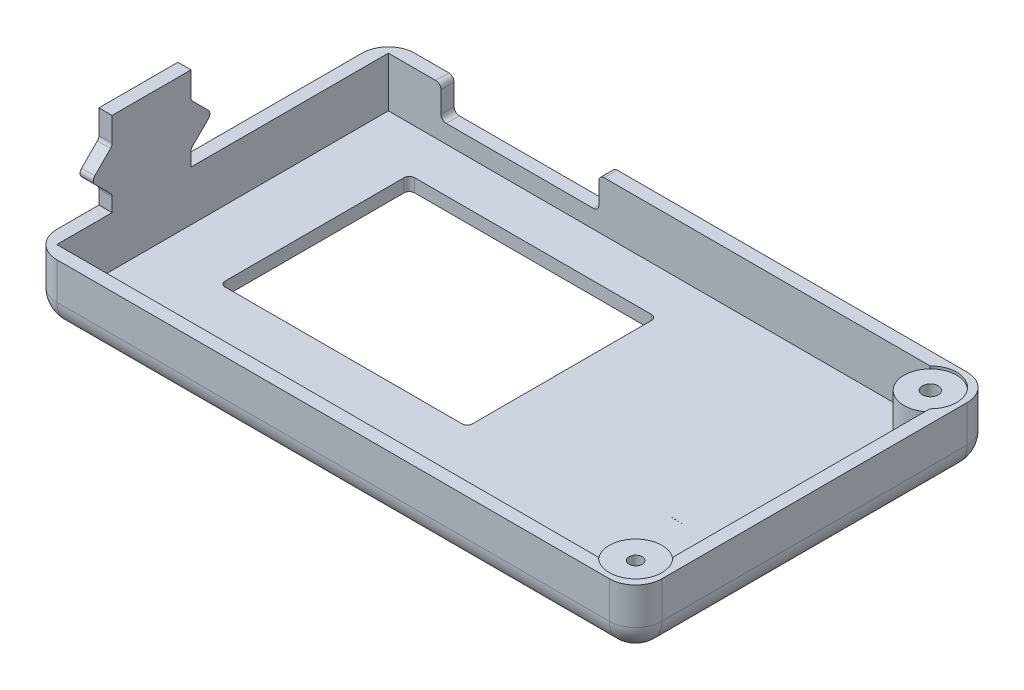
SolidWorks part; units mm, degrees
ref_plane "Front Plane" through (0, 0, 0) normal (0, 0, 1) x (1, 0, 0)
ref_plane "Top Plane" through (0, 0, 0) normal (0, 1, 0) x (1, 0, 0)
ref_plane "Right Plane" through (0, 0, 0) normal (1, 0, 0) x (0, 0, -1)
sketch "Sketch1" plane through (0, 0, 0) normal (0, 1, 0) x (1, 0, 0)
  line L1 (-57.5, -34) -> (57.5, -34)
  line L2 (-57.5, -34) -> (-57.5, 34)
  line L3 (-57.5, 34) -> (57.5, 34)
  line L4 (57.5, -34) -> (57.5, 34)
  line L5 (-57.5, -34) -> (57.5, 34) construction
  line L6 (-57.5, 34) -> (57.5, -34) construction
  point P0 (0, 0)
  dimension "D1" = 115
  dimension "D2" = 68
extrude "Boss-Extrude1" add sketch "Sketch1" along normal blind 28
shell "Shell2" thickness 2.5
sketch "Sketch9" plane through (-57.5, 0, 0) normal (-1, 0, 0) x (0, 0, 1)
  line L0 (-34, 12) -> (6, 12)
  line L1 (-34, 28) -> (-34, 0) construction
  line L2 (6, 12) -> (6, 15)
  line L3 (6, 15) -> (2, 19)
  line L4 (2, 19) -> (6, 23)
  line L5 (6, 23) -> (6, 28)
  line L6 (-34, 28) -> (34, 28) construction
  line L7 (6, 28) -> (21, 28)
  line L8 (21, 28) -> (21, 23)
  line L9 (21, 15) -> (25, 19)
  line L10 (25, 19) -> (21, 23)
  line L11 (21, 15) -> (21, 12)
  line L12 (21, 12) -> (34, 12)
  line L13 (34, 28) -> (34, 0) construction
  line L14 (34, 12) -> (34, 34)
  line L15 (34, 34) -> (-34, 34)
  line L16 (-34, 34) -> (-34, 12)
  line L17 (-34, 0) -> (34, 0) construction
  dimension "D1" = 3
  dimension "D2" = 12
  dimension "D3" = 4
  dimension "D4" = 15
  dimension "D5" = 22
  dimension "D6" = 4
  dimension "D7" = 13
extrude "Cut-Extrude8" cut sketch "Sketch9" against normal through all
sketch "Sketch10" plane through (57.5, 0, 0) normal (1, 0, 0) x (0, 0, -1)
  line L0 (-24.9917, 12) -> (1.2258, 12)
  line L1 (-21, 12) -> (-34, 12) construction
  line L2 (34, 12) -> (-6, 12) construction
  line L3 (1.2258, 12) -> (1.2258, 35)
  line L4 (1.2258, 35) -> (-24.9917, 35)
  line L5 (-24.9917, 35) -> (-24.9917, 12)
  dimension "D1" = 23
extrude "Cut-Extrude9" cut sketch "Sketch10" against normal up to next
fillet "Fillet3" radius 5 8 edges at (0, 0, 34) (57.5, 6, 34) (57.5, 0, 0) (57.5, 6, -34) (0, 0, -34) (-57.5, 6, -34) (-57.5, 0, 0) (-57.5, 6, 34)
fillet "Fillet4" radius 1 6 edges at (-56.25, 19, 25) (-56.25, 23, 21) (-56.25, 15, 21) (-56.25, 15, 6) (-56.25, 23, 6) (-56.25, 19, 2)
sketch "Sketch11" plane through (0, 2.5, 0) normal (0, 1, 0) x (1, 0, 0)
  line L0 (57.5, 29) -> (57.5, -29) construction
  line L1 (52.5, 34) -> (-52.5, 34) construction
  line L2 (52.5, -34) -> (-52.5, -34) construction
  circle A0 centre (51.5, 28) radius 5
  circle A1 centre (51.5, -28) radius 5
  dimension "D1" = 10
  dimension "D4" = 10
  dimension "D2" = 6
  dimension "D3" = 6
  dimension "D5" = 6
  dimension "D6" = 6
extrude "Boss-Extrude3" add sketch "Sketch11" along normal up to surface (9.5 mm away) up to face at (-14.0625, 12, 3.375)
sketch "Sketch12" plane through (0, 12, 0) normal (0, 1, 0) x (1, 0, 0)
  circle A0 centre (51.5, 28) radius 5
  circle A1 centre (51.5, -28) radius 5
  dimension "D1" = 10
  dimension "D2" = 10
extrude "Cut-Extrude10" cut sketch "Sketch12" against normal blind 0.5
sketch "Sketch13" plane through (0, 11.5, 0) normal (0, 1, 0) x (1, 0, 0)
  circle A0 centre (51.5, -28) radius 1.25
  dimension "D1" = 2.5
extrude "Cut-Extrude11" cut sketch "Sketch13" against normal through all
sketch "Sketch15" plane through (0, 11.5, 0) normal (0, 1, 0) x (1, 0, 0)
  circle A0 centre (51.5, 28) radius 1.5
  dimension "D1" = 3
extrude "Cut-Extrude12" cut sketch "Sketch15" against normal through all
sketch "Sketch17" plane through (0, 0, 0) normal (0, -1, 0) x (1, 0, 0)
  line L0 (52.5, -34) -> (-52.5, -34) construction
  line L1 (-41.5, 13) -> (3.5, 13)
  line L2 (-42.5, 12) -> (-42.5, -22)
  line L3 (-41.5, -23) -> (3.5, -23)
  line L4 (4.5, 12) -> (4.5, -22)
  line L5 (-57.5, -29) -> (-57.5, 29) construction
  arc A0 (3.5, 13) -> (4.5, 12) centre (3.5, 12) cw
  arc A1 (3.5, -23) -> (4.5, -22) centre (3.5, -22) ccw
  arc A2 (-42.5, -22) -> (-41.5, -23) centre (-41.5, -22) ccw
  arc A3 (-42.5, 12) -> (-41.5, 13) centre (-41.5, 12) cw
  point P10 (4.5, 13)
  point P13 (4.5, -23)
  point P18 (-42.5, 13)
  dimension "D5" = 1
  dimension "D1" = 47
  dimension "D2" = 36
  dimension "D3" = 11
  dimension "D4" = 15
extrude "Cut-Extrude13" cut sketch "Sketch17" against normal through all contours L4 A1 L3 A2 L2 A3 L1 A0
sketch "Sketch18" plane through (0, 0, -34) normal (0, 0, -1) x (-1, 0, 0)
  line L0 (15, 12) -> (15, 5.9385)
  line L2 (-52.5, 12) -> (52.5, 12) construction
  line L3 (15, 5.9385) -> (45, 5.9385)
  line L4 (45, 5.9385) -> (45, 12)
  line L5 (45, 12) -> (15, 12)
  line L6 (57.5, 12) -> (57.5, 5) construction
  dimension "D1" = 12.5
  dimension "D2" = 30
extrude "Cut-Extrude14" cut sketch "Sketch18" against normal up to next (2.5 mm away) contours L3 L4 L5 L0
fillet "Fillet5" radius 1 4 edges at (-15, 5.9385, -32.75) (-15, 12, -32.75) (-45, 12, -32.75) (-45, 5.9385, -32.75)
